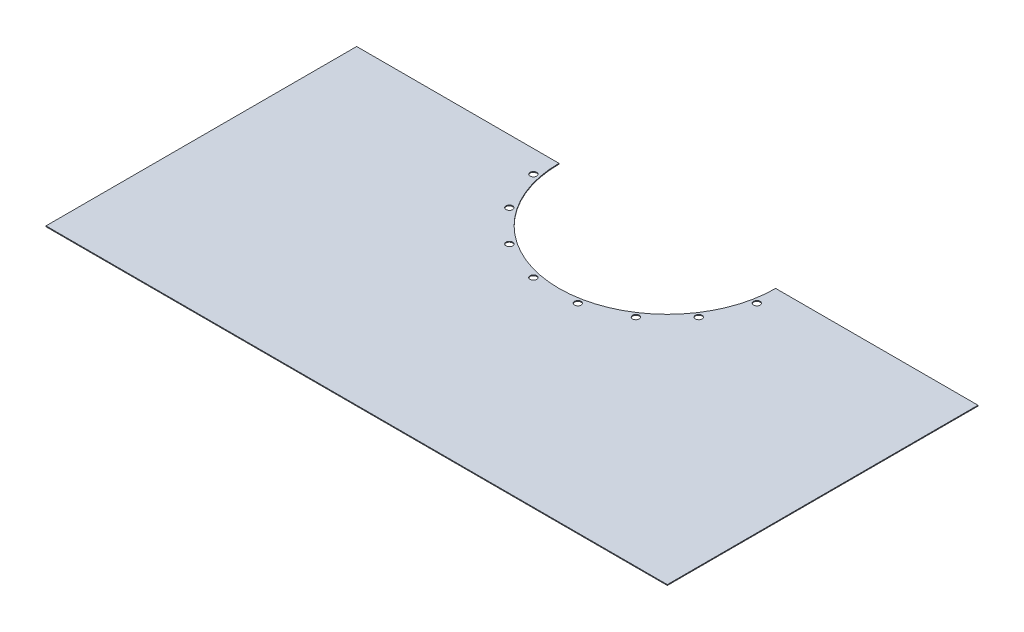
SolidWorks part; units mm, degrees
material "Perspex (TM) GS Acrylic Cast Sheet"
ref_plane "Front Plane" through (0, 0, 0) normal (0, 0, 1) x (1, 0, 0)
ref_plane "Top Plane" through (0, 0, 0) normal (0, 1, 0) x (1, 0, 0)
ref_plane "Right Plane" through (0, 0, 0) normal (1, 0, 0) x (0, 0, -1)
sketch "Sketch2" plane through (0, 0, 0) normal (0, 1, 0) x (1, 0, 0)
  line L0 (0, 0) -> (862.8324, 0) construction
  line L1 (0, 0) -> (219.2055, 43.6027) construction
  line L2 (0, 0) -> (219.2055, -43.6027) construction
  line L3 (219.2055, 43.6027) -> (223.5, 0)
  line L4 (223.5, 0) -> (219.2055, -43.6027) construction
  line L5 (-609.6, 0) -> (-212.625, 0)
  line L6 (-609.6, 0) -> (-609.6, -609.6)
  line L7 (-609.6, -609.6) -> (609.6, -609.6)
  line L8 (609.6, -609.6) -> (609.6, 0)
  line L9 (212.625, 0) -> (609.6, 0)
  circle A0 centre (0, 0) radius 223.5 construction
  circle A1 centre (219.2055, 43.6027) radius 6.5 construction
  circle A2 centre (219.2055, -43.6027) radius 6.5
  circle A3 centre (185.8335, -124.1699) radius 6.5
  circle A4 centre (124.1699, -185.8335) radius 6.5
  circle A5 centre (43.6027, -219.2055) radius 6.5
  circle A6 centre (-43.6027, -219.2055) radius 6.5
  circle A7 centre (-124.1699, -185.8335) radius 6.5
  circle A8 centre (-185.8335, -124.1699) radius 6.5
  circle A9 centre (-219.2055, -43.6027) radius 6.5
  circle A10 centre (-219.2055, 43.6027) radius 6.5 construction
  circle A11 centre (-185.8335, 124.1699) radius 6.5 construction
  circle A12 centre (-124.1699, 185.8335) radius 6.5 construction
  circle A13 centre (-43.6027, 219.2055) radius 6.5 construction
  circle A14 centre (43.6027, 219.2055) radius 6.5 construction
  circle A15 centre (124.1699, 185.8335) radius 6.5 construction
  circle A16 centre (185.8335, 124.1699) radius 6.5 construction
  arc A17 (-212.625, 0) -> (212.625, 0) centre (0, 0) ccw
  point P39 (0, 0)
  point P45 (0, 0)
  dimension "D1" = 447
  dimension "D2" = 13
  dimension "D6" = 425.25
  dimension "D4" = 1219.2
  dimension "D5" = 609.6
  dimension "D3" = 16
extrude "Boss-Extrude2" add sketch "Sketch2" along normal blind 1.5875 contours A17 L5 L6 L7 L8 L9 A9 A8 A7 A6 A5 A4 A3 A2
